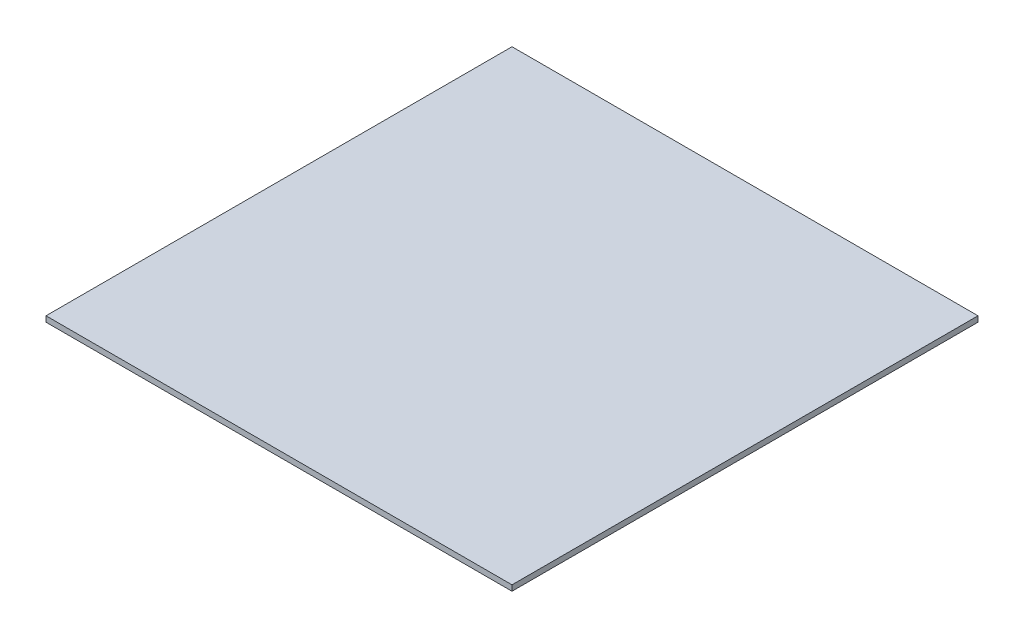
SolidWorks part; units mm, degrees
ref_plane "Front Plane" through (0, 0, 0) normal (0, 0, 1) x (1, 0, 0)
ref_plane "Top Plane" through (0, 0, 0) normal (0, 1, 0) x (1, 0, 0)
ref_plane "Right Plane" through (0, 0, 0) normal (1, 0, 0) x (0, 0, -1)
sketch "Sketch1" plane through (0, 0, 0) normal (0, 1, 0) x (1, 0, 0)
  line L1 (-125, 125) -> (125, 125)
  line L2 (-125, 125) -> (-125, -125)
  line L3 (-125, -125) -> (125, -125)
  line L4 (125, 125) -> (125, -125)
  line L5 (-125, 125) -> (125, -125) construction
  line L6 (-125, -125) -> (125, 125) construction
  point P0 (0, 0)
  dimension "D1" = 250
extrude "Boss-Extrude1" add sketch "Sketch1" along normal blind 3
sketch "Sketch2" plane through (0, 0, 0) normal (0, -1, 0) x (1, 0, 0)
  line L1 (75, 0) -> (-37.5, 64.9519)
  line L2 (-37.5, 64.9519) -> (-37.5, -64.9519)
  line L3 (-37.5, -64.9519) -> (75, 0)
  circle A1 centre (0, 0) radius 75 construction
  dimension "D1" = 150
sketch "Sketch3" plane through (0, 3, 0) normal (0, 1, 0) x (1, 0, 0)
  circle A0 centre (0, 0) radius 6.9561
extrude "Boss-Extrude2" [suppressed] add sketch "Sketch3" along normal blind 283
equation "\"motorDiam\"= 150"
equation "\"D1@Sketch2\"=\"motorDiam\""
